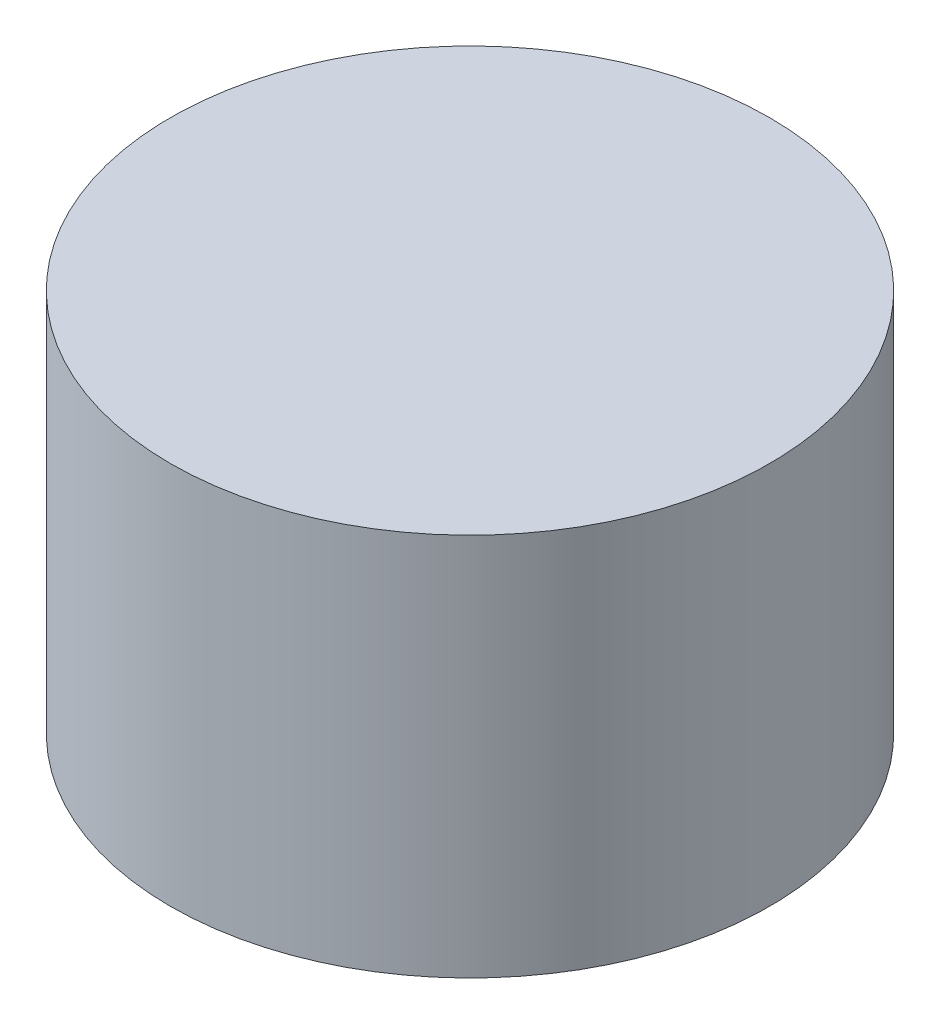
SolidWorks part; units mm, degrees
ref_plane "Front Plane" through (0, 0, 0) normal (0, 0, 1) x (1, 0, 0)
ref_plane "Top Plane" through (0, 0, 0) normal (0, 1, 0) x (1, 0, 0)
ref_plane "Right Plane" through (0, 0, 0) normal (1, 0, 0) x (0, 0, -1)
sketch "Sketch1" plane through (0, 0, 0) normal (1, 0, 0) x (0, 0, -1)
  line L0 (0, 0) -> (1612.9, 0)
  line L1 (1612.9, 0) -> (1612.9, -2064.512)
  line L2 (1612.9, -2064.512) -> (1451.61, -2064.512)
  line L3 (1451.61, -2064.512) -> (1451.61, -482.6)
  line L4 (1451.61, -482.6) -> (0, -482.6)
  line L5 (0, -482.6) -> (0, 0)
  dimension "D1" = 482.6
  dimension "D2" = 1612.9
  dimension "D3" = 2064.512
  dimension "D4" = 161.29
revolve "Revolve1" add sketch "Sketch1" angle 360 about L5
